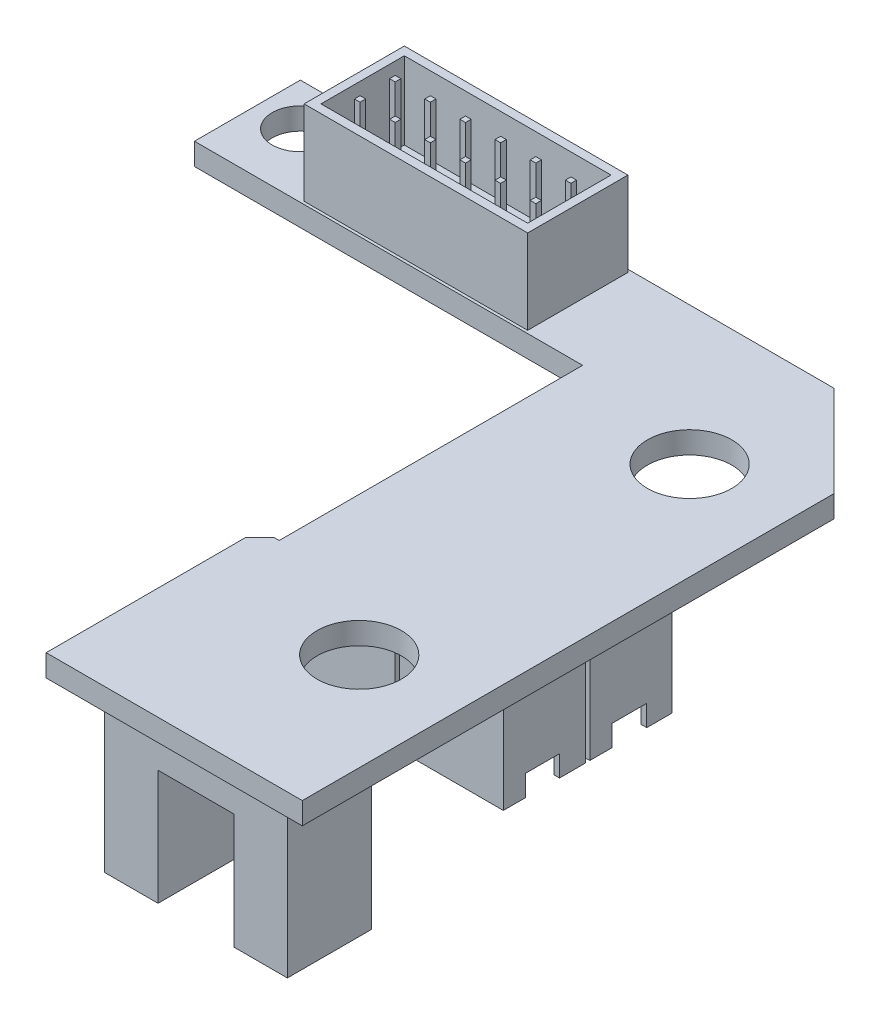
SolidWorks part; units mm, degrees
ref_plane "Спереди" through (0, 0, 0) normal (0, 0, 1) x (1, 0, 0)
ref_plane "Сверху" through (0, 0, 0) normal (0, 1, 0) x (1, 0, 0)
ref_plane "Справа" through (0, 0, 0) normal (1, 0, 0) x (0, 0, -1)
ref_plane "Плоскость1" through (0, -1.56, 0) normal (0, -1, 0) x (1, 0, 0)
sketch "Эскиз1" plane through (0, -1.56, 0) normal (0, -1, 0) x (1, 0, 0)
  line L0 (-16.84, 29.11) -> (-16.84, 0)
  line L1 (-16.84, 0) -> (0, 0)
  line L2 (0, 0) -> (0, 44.31)
  line L3 (0, 44.31) -> (-18.22, 44.31)
  line L4 (-18.22, 44.31) -> (-18.22, 30.11)
  line L5 (-18.22, 30.11) -> (-17.22, 29.11)
  line L6 (-17.22, 29.11) -> (-16.84, 29.11)
extrude "Бобышка-Вытянуть1" add sketch "Эскиз1" against normal blind 1.56
sketch "Эскиз2" plane through (-16.84, 0, 0) normal (-1, 0, 0) x (0, 0, 1)
  line L0 (0, 0) -> (7.53, 0)
  line L1 (7.53, 0) -> (7.53, -1.56)
  line L2 (7.53, -1.56) -> (0, -1.56)
  line L3 (0, -1.56) -> (0, 0)
extrude "Бобышка-Вытянуть2" add sketch "Эскиз2" along normal blind 27.61
sketch "Эскиз3" plane through (0, -1.56, 0) normal (0, -1, 0) x (1, 0, 0)
  line L0 (-16.34, 29.21) -> (-8.5, 29.21)
  line L1 (-8.5, 29.21) -> (-8.5, 23.36)
  line L2 (-8.5, 23.36) -> (-16.34, 23.36)
  line L3 (-16.34, 23.36) -> (-16.34, 29.21)
extrude "Бобышка-Вытянуть3" add sketch "Эскиз3" along normal blind 7
sketch "Эскиз4" plane through (0, -8.56, 0) normal (0, -1, 0) x (1, 0, 0)
  line L0 (-8.9, 23.76) -> (-8.9, 28.81)
  line L1 (-8.9, 28.81) -> (-15.94, 28.81)
  line L2 (-15.94, 28.81) -> (-15.94, 23.76)
  line L3 (-15.94, 23.76) -> (-8.9, 23.76)
extrude "Вырез-Вытянуть1" cut sketch "Эскиз4" against normal blind 6
sketch "Эскиз5" plane through (-15.94, 0, 0) normal (1, 0, 0) x (0, 0, -1)
  line L0 (-27.6277, -8.56) -> (-25.2131, -8.56)
  line L1 (-25.2131, -8.56) -> (-25.2131, -7.06)
  line L2 (-25.2131, -7.06) -> (-27.6277, -7.06)
  line L3 (-27.6277, -7.06) -> (-27.6277, -8.56)
extrude "Вырез-Вытянуть2" cut sketch "Эскиз5" against normal through all
sketch "Эскиз6" plane through (-8.5, 0, 0) normal (1, 0, 0) x (0, 0, -1)
  line L0 (-25.2131, -8.56) -> (-25.2131, -7.06)
  line L1 (-25.2131, -7.06) -> (-27.6277, -7.06)
  line L2 (-27.6277, -7.06) -> (-27.6277, -8.56)
  line L3 (-27.6277, -8.56) -> (-25.2131, -8.56)
extrude "Вырез-Вытянуть3" cut sketch "Эскиз6" against normal through all
sketch "Эскиз7" plane through (0, -1.56, 0) normal (0, -1, 0) x (1, 0, 0)
  line L0 (-8.2, 23.06) -> (-0.8, 23.06)
  line L1 (-0.8, 23.06) -> (-0.8, 17.21)
  line L2 (-0.8, 17.21) -> (-8.2, 17.21)
  line L3 (-8.2, 17.21) -> (-8.2, 23.06)
extrude "Бобышка-Вытянуть4" add sketch "Эскиз7" along normal blind 7
sketch "Эскиз8" plane through (0, -8.56, 0) normal (0, -1, 0) x (1, 0, 0)
  line L0 (-1.2, 17.61) -> (-1.2, 22.66)
  line L1 (-1.2, 22.66) -> (-7.8, 22.66)
  line L2 (-7.8, 22.66) -> (-7.8, 17.61)
  line L3 (-7.8, 17.61) -> (-1.2, 17.61)
extrude "Вырез-Вытянуть4" cut sketch "Эскиз8" against normal blind 6
sketch "Эскиз9" plane through (-7.8, 0, 0) normal (1, 0, 0) x (0, 0, -1)
  line L0 (-21.4663, -8.56) -> (-19.01, -8.56)
  line L1 (-19.01, -8.56) -> (-19.01, -7.06)
  line L2 (-19.01, -7.06) -> (-21.4663, -7.06)
  line L3 (-21.4663, -7.06) -> (-21.4663, -8.56)
extrude "Вырез-Вытянуть5" cut sketch "Эскиз9" against normal through all
sketch "Эскиз10" plane through (-0.8, 0, 0) normal (1, 0, 0) x (0, 0, -1)
  line L0 (-19.01, -8.56) -> (-19.01, -7.06)
  line L1 (-19.01, -7.06) -> (-21.4663, -7.06)
  line L2 (-21.4663, -7.06) -> (-21.4663, -8.56)
  line L3 (-21.4663, -8.56) -> (-19.01, -8.56)
extrude "Вырез-Вытянуть6" cut sketch "Эскиз10" against normal through all
sketch "Эскиз11" plane through (0, -1.56, 0) normal (0, -1, 0) x (1, 0, 0)
  line L0 (-8.2, 29.21) -> (-0.8, 29.21)
  line L1 (-0.8, 29.21) -> (-0.8, 23.36)
  line L2 (-0.8, 23.36) -> (-8.2, 23.36)
  line L3 (-8.2, 23.36) -> (-8.2, 29.21)
extrude "Бобышка-Вытянуть5" add sketch "Эскиз11" along normal blind 7
sketch "Эскиз12" plane through (0, -8.56, 0) normal (0, -1, 0) x (1, 0, 0)
  line L0 (-1.2, 23.76) -> (-1.2, 28.81)
  line L1 (-1.2, 28.81) -> (-7.8, 28.81)
  line L2 (-7.8, 28.81) -> (-7.8, 23.76)
  line L3 (-7.8, 23.76) -> (-1.2, 23.76)
extrude "Вырез-Вытянуть7" cut sketch "Эскиз12" against normal blind 6
sketch "Эскиз13" plane through (-7.8, 0, 0) normal (1, 0, 0) x (0, 0, -1)
  line L0 (-27.6277, -8.56) -> (-25.2131, -8.56)
  line L1 (-25.2131, -8.56) -> (-25.2131, -7.06)
  line L2 (-25.2131, -7.06) -> (-27.6277, -7.06)
  line L3 (-27.6277, -7.06) -> (-27.6277, -8.56)
extrude "Вырез-Вытянуть8" cut sketch "Эскиз13" against normal through all
sketch "Эскиз14" plane through (-0.8, 0, 0) normal (1, 0, 0) x (0, 0, -1)
  line L0 (-25.2131, -8.56) -> (-25.2131, -7.06)
  line L1 (-25.2131, -7.06) -> (-27.6277, -7.06)
  line L2 (-27.6277, -7.06) -> (-27.6277, -8.56)
  line L3 (-27.6277, -8.56) -> (-25.2131, -8.56)
extrude "Вырез-Вытянуть9" cut sketch "Эскиз14" against normal through all
sketch "Эскиз15" plane through (0, -1.56, 0) normal (0, -1, 0) x (1, 0, 0)
  line L0 (-16.34, 23.06) -> (-8.5, 23.06)
  line L1 (-8.5, 23.06) -> (-8.5, 17.21)
  line L2 (-8.5, 17.21) -> (-16.34, 17.21)
  line L3 (-16.34, 17.21) -> (-16.34, 23.06)
extrude "Бобышка-Вытянуть6" add sketch "Эскиз15" along normal blind 7
sketch "Эскиз16" plane through (0, -8.56, 0) normal (0, -1, 0) x (1, 0, 0)
  line L0 (-8.9, 17.61) -> (-8.9, 22.66)
  line L1 (-8.9, 22.66) -> (-15.94, 22.66)
  line L2 (-15.94, 22.66) -> (-15.94, 17.61)
  line L3 (-15.94, 17.61) -> (-8.9, 17.61)
extrude "Вырез-Вытянуть10" cut sketch "Эскиз16" against normal blind 6
sketch "Эскиз17" plane through (-15.94, 0, 0) normal (1, 0, 0) x (0, 0, -1)
  line L0 (-21.4663, -8.56) -> (-19.01, -8.56)
  line L1 (-19.01, -8.56) -> (-19.01, -7.06)
  line L2 (-19.01, -7.06) -> (-21.4663, -7.06)
  line L3 (-21.4663, -7.06) -> (-21.4663, -8.56)
extrude "Вырез-Вытянуть11" cut sketch "Эскиз17" against normal through all
sketch "Эскиз18" plane through (-8.5, 0, 0) normal (1, 0, 0) x (0, 0, -1)
  line L0 (-19.01, -8.56) -> (-19.01, -7.06)
  line L1 (-19.01, -7.06) -> (-21.4663, -7.06)
  line L2 (-21.4663, -7.06) -> (-21.4663, -8.56)
  line L3 (-21.4663, -8.56) -> (-19.01, -8.56)
extrude "Вырез-Вытянуть12" cut sketch "Эскиз18" against normal through all
sketch "Эскиз19" plane through (0, -1.56, 0) normal (0, -1, 0) x (1, 0, 0)
  line L0 (-14.16, 44.21) -> (-1.16, 44.21)
  line L1 (-1.16, 44.21) -> (-1.16, 38.21)
  line L2 (-1.16, 38.21) -> (-14.16, 38.21)
  line L3 (-14.16, 38.21) -> (-14.16, 44.21)
extrude "Бобышка-Вытянуть7" add sketch "Эскиз19" along normal blind 10
sketch "Эскиз20" plane through (0, 0, 44.21) normal (0, 0, 1) x (1, 0, 0)
  line L0 (-10.36, -11.56) -> (-4.96, -11.56)
  line L1 (-4.96, -11.56) -> (-4.96, -3.36)
  line L2 (-4.96, -3.36) -> (-10.36, -3.36)
  line L3 (-10.36, -3.36) -> (-10.36, -11.56)
extrude "Вырез-Вытянуть13" cut sketch "Эскиз20" against normal up to next
sketch "Эскиз21" plane through (0, -2.56, 0) normal (0, -1, 0) x (1, 0, 0)
  line L0 (-5.6821, 26.0347) -> (-6.5197, 26.0347)
  line L1 (-6.5197, 26.0347) -> (-6.5197, 26.5794)
  line L2 (-6.5197, 26.5794) -> (-5.6821, 26.5794)
  line L3 (-5.6821, 26.5794) -> (-5.6821, 26.0347)
extrude "Бобышка-Вытянуть8" add sketch "Эскиз21" along normal blind 4.5
sketch "Эскиз22" plane through (0, -2.56, 0) normal (0, -1, 0) x (1, 0, 0)
  line L0 (-13.6821, 26.0347) -> (-14.5197, 26.0347)
  line L1 (-14.5197, 26.0347) -> (-14.5197, 26.5794)
  line L2 (-14.5197, 26.5794) -> (-13.6821, 26.5794)
  line L3 (-13.6821, 26.5794) -> (-13.6821, 26.0347)
extrude "Бобышка-Вытянуть9" add sketch "Эскиз22" along normal blind 4.5
sketch "Эскиз23" plane through (0, -2.56, 0) normal (0, -1, 0) x (1, 0, 0)
  line L0 (-2.4603, 26.0347) -> (-3.2982, 26.0347)
  line L1 (-3.2982, 26.0347) -> (-3.2982, 26.5794)
  line L2 (-3.2982, 26.5794) -> (-2.4603, 26.5794)
  line L3 (-2.4603, 26.5794) -> (-2.4603, 26.0347)
extrude "Бобышка-Вытянуть10" add sketch "Эскиз23" along normal blind 4.5
sketch "Эскиз24" plane through (0, -2.56, 0) normal (0, -1, 0) x (1, 0, 0)
  line L0 (-10.4603, 26.0347) -> (-11.2982, 26.0347)
  line L1 (-11.2982, 26.0347) -> (-11.2982, 26.5794)
  line L2 (-11.2982, 26.5794) -> (-10.4603, 26.5794)
  line L3 (-10.4603, 26.5794) -> (-10.4603, 26.0347)
extrude "Бобышка-Вытянуть11" add sketch "Эскиз24" along normal blind 4.5
sketch "Эскиз25" plane through (0, -2.56, 0) normal (0, -1, 0) x (1, 0, 0)
  line L0 (-13.6821, 20.0347) -> (-14.5197, 20.0347)
  line L1 (-14.5197, 20.0347) -> (-14.5197, 20.5794)
  line L2 (-14.5197, 20.5794) -> (-13.6821, 20.5794)
  line L3 (-13.6821, 20.5794) -> (-13.6821, 20.0347)
extrude "Бобышка-Вытянуть12" add sketch "Эскиз25" along normal blind 4.5
sketch "Эскиз26" plane through (0, -2.56, 0) normal (0, -1, 0) x (1, 0, 0)
  line L0 (-5.6821, 20.0347) -> (-6.5197, 20.0347)
  line L1 (-6.5197, 20.0347) -> (-6.5197, 20.5794)
  line L2 (-6.5197, 20.5794) -> (-5.6821, 20.5794)
  line L3 (-5.6821, 20.5794) -> (-5.6821, 20.0347)
extrude "Бобышка-Вытянуть13" add sketch "Эскиз26" along normal blind 4.5
sketch "Эскиз27" plane through (0, -2.56, 0) normal (0, -1, 0) x (1, 0, 0)
  line L0 (-10.4603, 20.0347) -> (-11.2982, 20.0347)
  line L1 (-11.2982, 20.0347) -> (-11.2982, 20.5794)
  line L2 (-11.2982, 20.5794) -> (-10.4603, 20.5794)
  line L3 (-10.4603, 20.5794) -> (-10.4603, 20.0347)
extrude "Бобышка-Вытянуть14" add sketch "Эскиз27" along normal blind 4.5
sketch "Эскиз28" plane through (0, -2.56, 0) normal (0, -1, 0) x (1, 0, 0)
  line L0 (-2.4603, 20.0347) -> (-3.2982, 20.0347)
  line L1 (-3.2982, 20.0347) -> (-3.2982, 20.5794)
  line L2 (-3.2982, 20.5794) -> (-2.4603, 20.5794)
  line L3 (-2.4603, 20.5794) -> (-2.4603, 20.0347)
extrude "Бобышка-Вытянуть15" add sketch "Эскиз28" along normal blind 4.5
sketch "Эскиз29" plane through (0, 0, 0) normal (0, 1, 0) x (-1, 0, 0)
  line L0 (36.85, 7.33) -> (36.85, 0.2)
  line L1 (36.85, 0.2) -> (20.95, 0.2)
  line L2 (20.95, 0.2) -> (20.95, 7.33)
  line L3 (20.95, 7.33) -> (36.85, 7.33)
extrude "Бобышка-Вытянуть16" add sketch "Эскиз29" along normal blind 6
sketch "Эскиз30" plane through (0, 6, 0) normal (0, 1, 0) x (-1, 0, 0)
  line L0 (36.25, 0.8) -> (36.25, 6.73)
  line L1 (36.25, 6.73) -> (21.55, 6.73)
  line L2 (21.55, 6.73) -> (21.55, 0.8)
  line L3 (21.55, 0.8) -> (36.25, 0.8)
extrude "Вырез-Вытянуть14" cut sketch "Эскиз30" against normal blind 5.5
sketch "Эскиз31" plane through (0, 0.5, 0) normal (0, 1, 0) x (-1, 0, 0)
  line L0 (22.8642, 5.2366) -> (22.8642, 4.8366)
  line L1 (22.8642, 4.8366) -> (22.4642, 4.8366)
  line L2 (22.4642, 4.8366) -> (22.4642, 5.2366)
  line L3 (22.4642, 5.2366) -> (22.8642, 5.2366)
extrude "Бобышка-Вытянуть17" add sketch "Эскиз31" along normal blind 5.5
sketch "Эскиз32" plane through (0, 0.5, 0) normal (0, 1, 0) x (-1, 0, 0)
  line L0 (25.3642, 5.2366) -> (25.3642, 4.8366)
  line L1 (25.3642, 4.8366) -> (24.9642, 4.8366)
  line L2 (24.9642, 4.8366) -> (24.9642, 5.2366)
  line L3 (24.9642, 5.2366) -> (25.3642, 5.2366)
extrude "Бобышка-Вытянуть18" add sketch "Эскиз32" along normal blind 5.5
sketch "Эскиз33" plane through (0, 0.5, 0) normal (0, 1, 0) x (-1, 0, 0)
  line L0 (27.8642, 5.2366) -> (27.8642, 4.8366)
  line L1 (27.8642, 4.8366) -> (27.4642, 4.8366)
  line L2 (27.4642, 4.8366) -> (27.4642, 5.2366)
  line L3 (27.4642, 5.2366) -> (27.8642, 5.2366)
extrude "Бобышка-Вытянуть19" add sketch "Эскиз33" along normal blind 5.5
sketch "Эскиз34" plane through (0, 0.5, 0) normal (0, 1, 0) x (-1, 0, 0)
  line L0 (30.3642, 5.2366) -> (30.3642, 4.8366)
  line L1 (30.3642, 4.8366) -> (29.9642, 4.8366)
  line L2 (29.9642, 4.8366) -> (29.9642, 5.2366)
  line L3 (29.9642, 5.2366) -> (30.3642, 5.2366)
extrude "Бобышка-Вытянуть20" add sketch "Эскиз34" along normal blind 5.5
sketch "Эскиз35" plane through (0, 0.5, 0) normal (0, 1, 0) x (-1, 0, 0)
  line L0 (32.8642, 5.2366) -> (32.8642, 4.8366)
  line L1 (32.8642, 4.8366) -> (32.4642, 4.8366)
  line L2 (32.4642, 4.8366) -> (32.4642, 5.2366)
  line L3 (32.4642, 5.2366) -> (32.8642, 5.2366)
extrude "Бобышка-Вытянуть21" add sketch "Эскиз35" along normal blind 5.5
sketch "Эскиз36" plane through (0, 0.5, 0) normal (0, 1, 0) x (-1, 0, 0)
  line L0 (35.3642, 5.2366) -> (35.3642, 4.8366)
  line L1 (35.3642, 4.8366) -> (34.9642, 4.8366)
  line L2 (34.9642, 4.8366) -> (34.9642, 5.2366)
  line L3 (34.9642, 5.2366) -> (35.3642, 5.2366)
extrude "Бобышка-Вытянуть22" add sketch "Эскиз36" along normal blind 5.5
sketch "Эскиз37" plane through (0, 0.5, 0) normal (0, 1, 0) x (-1, 0, 0)
  line L0 (35.3642, 2.7366) -> (35.3642, 2.3366)
  line L1 (35.3642, 2.3366) -> (34.9642, 2.3366)
  line L2 (34.9642, 2.3366) -> (34.9642, 2.7366)
  line L3 (34.9642, 2.7366) -> (35.3642, 2.7366)
extrude "Бобышка-Вытянуть23" add sketch "Эскиз37" along normal blind 5.5
sketch "Эскиз38" plane through (0, 0.5, 0) normal (0, 1, 0) x (-1, 0, 0)
  line L0 (32.8642, 2.7366) -> (32.8642, 2.3366)
  line L1 (32.8642, 2.3366) -> (32.4642, 2.3366)
  line L2 (32.4642, 2.3366) -> (32.4642, 2.7366)
  line L3 (32.4642, 2.7366) -> (32.8642, 2.7366)
extrude "Бобышка-Вытянуть24" add sketch "Эскиз38" along normal blind 5.5
sketch "Эскиз39" plane through (0, 0.5, 0) normal (0, 1, 0) x (-1, 0, 0)
  line L0 (30.3642, 2.7366) -> (30.3642, 2.3366)
  line L1 (30.3642, 2.3366) -> (29.9642, 2.3366)
  line L2 (29.9642, 2.3366) -> (29.9642, 2.7366)
  line L3 (29.9642, 2.7366) -> (30.3642, 2.7366)
extrude "Бобышка-Вытянуть25" add sketch "Эскиз39" along normal blind 5.5
sketch "Эскиз40" plane through (0, 0.5, 0) normal (0, 1, 0) x (-1, 0, 0)
  line L0 (27.8642, 2.7366) -> (27.8642, 2.3366)
  line L1 (27.8642, 2.3366) -> (27.4642, 2.3366)
  line L2 (27.4642, 2.3366) -> (27.4642, 2.7366)
  line L3 (27.4642, 2.7366) -> (27.8642, 2.7366)
extrude "Бобышка-Вытянуть26" add sketch "Эскиз40" along normal blind 5.5
sketch "Эскиз41" plane through (0, 0.5, 0) normal (0, 1, 0) x (-1, 0, 0)
  line L0 (25.3642, 2.7366) -> (25.3642, 2.3366)
  line L1 (25.3642, 2.3366) -> (24.9642, 2.3366)
  line L2 (24.9642, 2.3366) -> (24.9642, 2.7366)
  line L3 (24.9642, 2.7366) -> (25.3642, 2.7366)
extrude "Бобышка-Вытянуть27" add sketch "Эскиз41" along normal blind 5.5
sketch "Эскиз42" plane through (0, 0.5, 0) normal (0, 1, 0) x (-1, 0, 0)
  line L0 (22.8642, 2.7366) -> (22.8642, 2.3366)
  line L1 (22.8642, 2.3366) -> (22.4642, 2.3366)
  line L2 (22.4642, 2.3366) -> (22.4642, 2.7366)
  line L3 (22.4642, 2.7366) -> (22.8642, 2.7366)
extrude "Бобышка-Вытянуть28" add sketch "Эскиз42" along normal blind 5.5
hole_wizard "Диаметр отверстия Ø4.0 (4)1" positions "Эскиз44" profile "Эскиз43" hole size "Ø4.0" standard "Ansi Metric"
sketch "Эскиз44" plane through (0, 0, 0) normal (0, 1, 0) x (1, 0, 0)
  point P0 (-41.45, -3)
sketch "Эскиз43" plane through (-41.45, 0, 3) normal (1, 0, 0) x (0, 0, 1)
  line L0 (0, 0) -> (0, 11.56)
  line L1 (0, 11.56) -> (2, 11.56)
  line L2 (2, 11.56) -> (2, 0)
  line L5 (2, 0) -> (0, 0)
  line L11 (0, -6.35) -> (0, 107.95) construction
  dimension "Диаметр сквозного отверстия" = 4
  dimension "Глубина сквозного отверстия" = 11.56
hole_wizard "Диаметр отверстия Ø6.0 (6)1" positions "Эскиз46" profile "Эскиз45" hole size "Ø6.0" standard "Ansi Metric"
sketch "Эскиз46" plane through (0, 0, 0) normal (0, 1, 0) x (1, 0, 0)
  point P0 (-6.95, -9.81)
  point P1 (-6.95, -33.31)
sketch "Эскиз45" plane through (-6.95, 0, 9.81) normal (1, 0, 0) x (0, 0, 1)
  line L0 (0, 0) -> (0, 11.56)
  line L1 (0, 11.56) -> (3, 11.56)
  line L2 (3, 11.56) -> (3, 0)
  line L5 (3, 0) -> (0, 0)
  line L11 (0, -6.35) -> (0, 107.95) construction
  dimension "Диаметр сквозного отверстия" = 6
  dimension "Глубина сквозного отверстия" = 11.56
chamfer "Фаска1" distance 6.5 angle 45 1 edges at (0, -0.78, 0)
